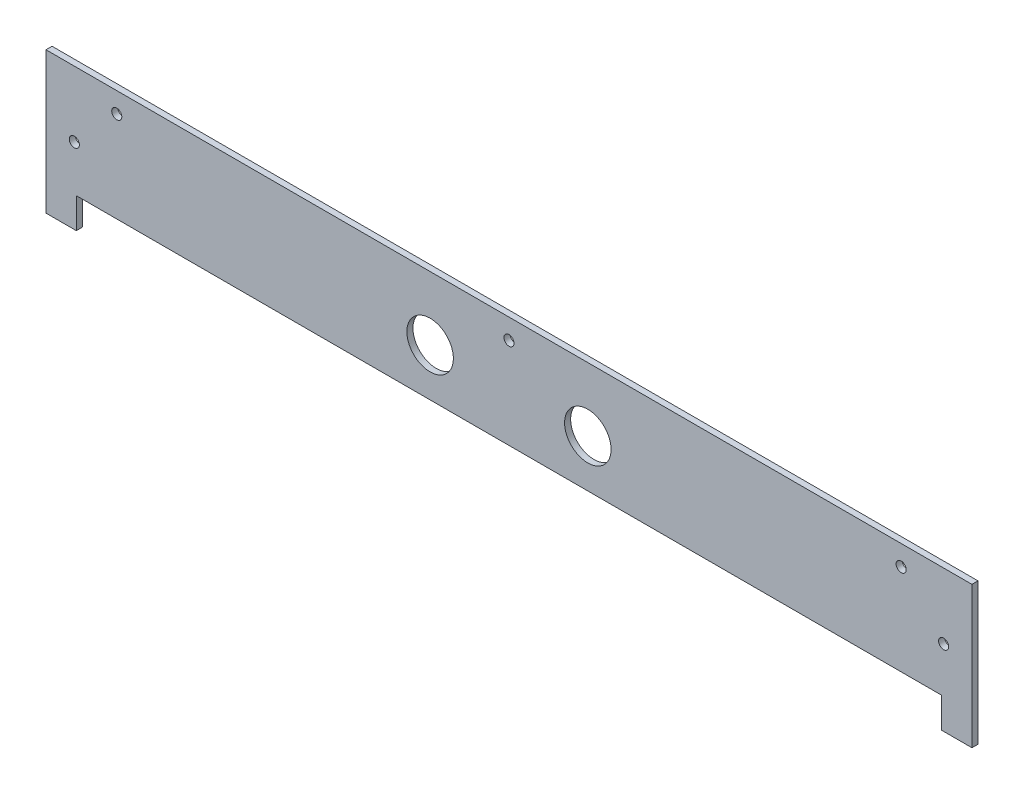
SolidWorks part; units mm, degrees
material "1345 Alloy"
ref_plane "Front Plane" through (0, 0, 0) normal (0, 0, 1) x (1, 0, 0)
ref_plane "Top Plane" through (0, 0, 0) normal (0, 1, 0) x (1, 0, 0)
ref_plane "Right Plane" through (0, 0, 0) normal (1, 0, 0) x (0, 0, -1)
sketch "Sketch1" plane through (0, 0, 0) normal (0, 0, 1) x (1, 0, 0)
  line L1 (-229, 122.5) -> (229, 122.5)
  line L2 (-229, 122.5) -> (-229, -122.5)
  line L3 (-229, -122.5) -> (229, -122.5)
  line L4 (229, 122.5) -> (229, -122.5)
  line L5 (-229, 122.5) -> (229, -122.5) construction
  line L6 (-229, -122.5) -> (229, 122.5) construction
  point P0 (0, 0)
  dimension "D1" = 458
  dimension "D2" = 245
extrude "Boss-Extrude1" add sketch "Sketch1" along normal blind 3
sketch "Sketch2" plane through (0, 0, 3) normal (0, 0, 1) x (1, 0, 0)
  line L0 (-229, -122.5) -> (-155, -122.5) construction
  line L2 (-155, -122.5) -> (-155, -107.5) construction
  line L3 (-155, -107.5) -> (-155, -122.5) construction
  line L6 (-148, -107.5) -> (-148, -122.5)
  line L11 (-162, -107.5) -> (-162, -122.5)
  line L12 (155, -122.5) -> (229, -122.5) construction
  line L13 (155, -107.5) -> (155, -122.5) construction
  line L14 (162, -107.5) -> (162, -122.5)
  line L15 (148, -107.5) -> (148, -122.5)
  line L16 (-155, -107.5) -> (155, -107.5) construction
  arc A4 (-148, -107.5) -> (-162, -107.5) centre (-155, -107.5) ccw
  arc A5 (-162, -122.5) -> (-148, -122.5) centre (-155, -122.5) ccw
  arc A6 (162, -107.5) -> (148, -107.5) centre (155, -107.5) ccw
  arc A7 (148, -122.5) -> (162, -122.5) centre (155, -122.5) ccw
  point P4 (-155, -115)
  point P13 (155, -115)
  dimension "D3" = 7
  dimension "D5" = 7
  dimension "D1" = 74
  dimension "D2" = 15
  dimension "D4" = 15
  dimension "D6" = 74
extrude "Cut-Extrude1" cut sketch "Sketch2" against normal through all
sketch "Sketch3" plane through (0, 0, 3) normal (0, 0, 1) x (1, 0, 0)
  line L19 (194, 112.5) -> (194, -107.5) construction
  line L20 (-215, 0) -> (-215, 90) construction
  line L21 (-215, 0) -> (-215, -90) construction
  line L25 (229, 0) -> (215, 0) construction
  line L26 (0, 112.5) -> (-194, 112.5) construction
  line L27 (-194, 112.5) -> (-194, -107.5) construction
  line L31 (215, 0) -> (215, 90) construction
  line L32 (215, 0) -> (215, -90) construction
  line L33 (0, 112.5) -> (194, 112.5) construction
  line L34 (0, 0) -> (0, 112.5) construction
  line L35 (0, 0) -> (0, -107.5) construction
  line L36 (-194, -107.5) -> (0, -107.5) construction
  line L37 (0, -107.5) -> (194, -107.5) construction
  line L38 (-194, 112.5) -> (-229, 112.5) construction
  line L39 (-229, 112.5) -> (-229, 122.5) construction
  circle A12 centre (-194, 112.5) radius 2.5
  circle A13 centre (-194, -107.5) radius 2.5
  circle A14 centre (194, -107.5) radius 2.5
  circle A15 centre (194, 112.5) radius 2.5
  circle A16 centre (-215, 0) radius 2.5
  circle A17 centre (-215, -90) radius 2.5
  circle A18 centre (-215, 90) radius 2.5
  circle A19 centre (215, 0) radius 2.5
  circle A20 centre (215, -90) radius 2.5
  circle A21 centre (215, 90) radius 2.5
  circle A22 centre (0, 112.5) radius 2.5
  circle A23 centre (0, -107.5) radius 2.5
  dimension "D3" = 5
  dimension "D6" = 90
  dimension "D9" = 5
  dimension "D12" = 90
  dimension "D15" = 5
  dimension "D16" = 194
  dimension "D17" = 194
  dimension "D2" = 5
  dimension "D4" = 5
  dimension "D5" = 5
  dimension "D8" = 5
  dimension "D10" = 5
  dimension "D14" = 5
  dimension "D7" = 90
  dimension "D11" = 14
  dimension "D13" = 90
  dimension "D18" = 194
  dimension "D19" = 194
extrude "Cut-Extrude2" cut sketch "Sketch3" against normal through all
sketch "Sketch4" plane through (0, 0, 3) normal (0, 0, 1) x (1, 0, 0)
  line L5 (0, 122.5) -> (0, 102.5) construction
  line L6 (229, 122.5) -> (-229, 122.5) construction
  line L7 (0, 102.5) -> (0, 82.5) construction
  line L8 (229, 91) -> (39, 91) construction
  line L10 (-39, 102.5) -> (-39, 122.5) construction
  line L11 (229, -122.5) -> (229, 122.5) construction
  line L12 (-229, 91) -> (-39, 91) construction
  line L13 (-229, 122.5) -> (-229, -122.5) construction
  line L14 (-39, 91) -> (0, 91) construction
  circle A1 centre (-39, 91) radius 11.5
  circle A2 centre (39, 91) radius 11.5
  dimension "D6" = 190
  dimension "D4" = 23
  dimension "D7" = 23
  dimension "D1" = 20
  dimension "D2" = 20
  dimension "D3" = 20
  dimension "D5" = 190
extrude "Cut-Extrude3" cut sketch "Sketch4" against normal through all
sketch "Sketch5" plane through (0, 0, 3) normal (0, 0, 1) x (1, 0, 0)
  line L0 (-229, -122) -> (-229, 53) construction
  line L1 (-229, 53) -> (229, 53) construction
  line L2 (-229, 53) -> (-229, 67.5) construction
  line L3 (-229, 67.5) -> (-214, 67.5) construction
  line L4 (229, 53) -> (229, 67.5) construction
  line L5 (229, 67.5) -> (214, 67.5) construction
  line L6 (214, 67.5) -> (-214, 67.5)
  line L7 (-214, 67.5) -> (-214, 38.5)
  line L8 (-214, 38.5) -> (214, 38.5)
  line L9 (214, 38.5) -> (214, 67.5)
  dimension "D1" = 175
  dimension "D2" = 14.5
  dimension "D3" = 15
  dimension "D4" = 14.5
  dimension "D5" = 15
  dimension "D6" = 29
extrude "Cut-Extrude4" cut sketch "Sketch5" against normal through all
sketch "Sketch8" plane through (0, 0, 3) normal (0, 0, 1) x (1, 0, 0)
  line L0 (-39, -5.5) -> (-39, 79.5) construction
  line L1 (-73.95, 15.1) -> (-4.05, 15.1)
  line L2 (-73.95, 15.1) -> (-73.95, -26.1)
  line L3 (-73.95, -26.1) -> (-4.05, -26.1)
  line L4 (-4.05, 15.1) -> (-4.05, -26.1)
  line L5 (-73.95, 15.1) -> (-4.05, -26.1) construction
  line L6 (-73.95, -26.1) -> (-4.05, 15.1) construction
  line L12 (5.6797, -26.0547) -> (-83.3, 14.88) construction
  line L13 (5.2962, 15.7036) -> (-83.368, -26.7379) construction
  circle A1 centre (-39, 91) radius 11.5 construction
  circle A2 centre (5.2962, 15.7036) radius 1.5
  circle A3 centre (5.6797, -26.0547) radius 1.5
  circle A4 centre (-83.3, 14.88) radius 1.5
  circle A5 centre (-83.368, -26.7379) radius 1.5
  point P0 (-39, -5.5)
  dimension "D6" = 3
  dimension "D7" = 3
  dimension "D8" = 3
  dimension "D9" = 3
  dimension "D1" = 69.9
  dimension "D2" = 41.2
  dimension "D3" = 85
  dimension "D4" = 88.6
  dimension "D5" = 41.76
extrude "Cut-Extrude5" cut sketch "Sketch8" against normal through all
sketch "Sketch9" plane through (0, 0, 3) normal (0, 0, 1) x (1, 0, 0)
  line L0 (-229, 122.5) -> (-229, 52.5) construction
  line L1 (-229, 122.5) -> (-229, -122.5) construction
  line L3 (-229, 52.5) -> (229, 52.5)
  line L4 (-229, 52.5) -> (-229, -122.5)
  line L5 (-229, -122.5) -> (229, -122.5)
  line L6 (229, 52.5) -> (229, -122.5)
  dimension "D1" = 70
extrude "Cut-Extrude7" cut sketch "Sketch9" against normal blind 10
